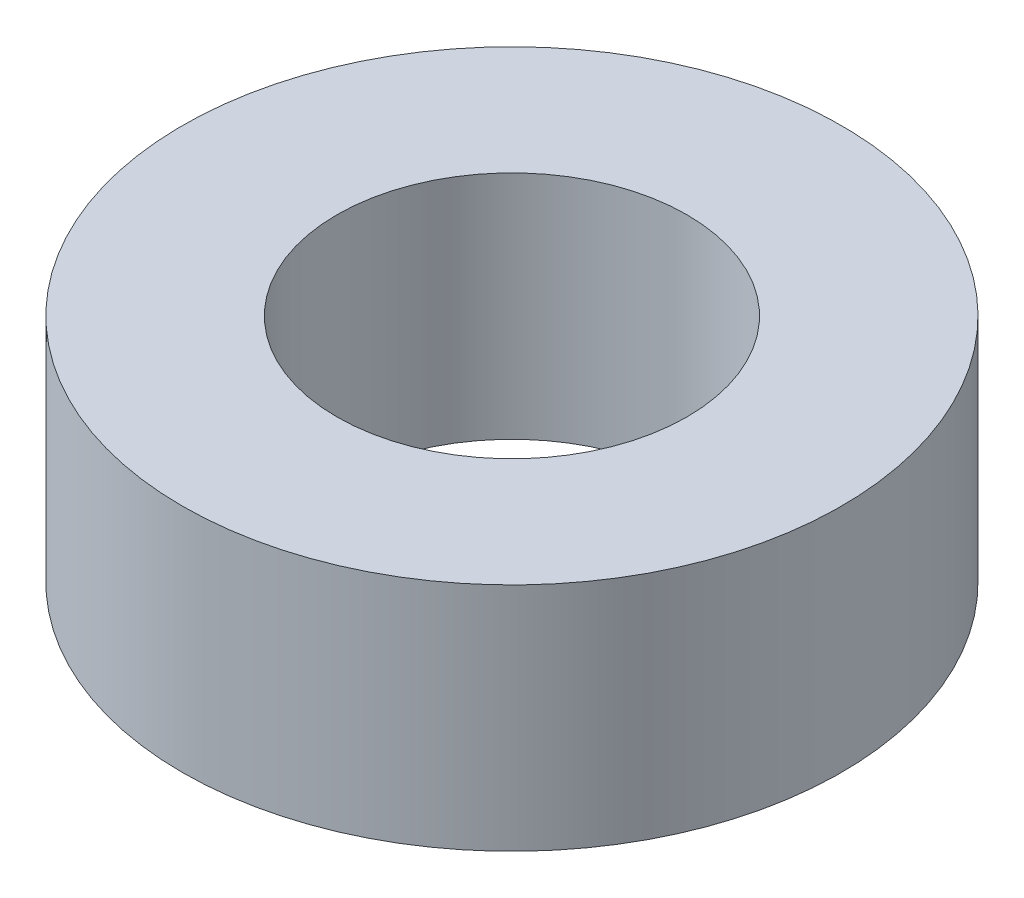
SolidWorks part; units mm, degrees
ref_plane "Alzado" through (0, 0, 0) normal (0, 0, 1) x (1, 0, 0)
ref_plane "Planta" through (0, 0, 0) normal (0, 1, 0) x (1, 0, 0)
ref_plane "Vista lateral" through (0, 0, 0) normal (1, 0, 0) x (0, 0, -1)
sketch "Croquis1" plane through (0, 0, 0) normal (0, 1, 0) x (1, 0, 0)
  circle A0 centre (0, 0) radius 4
  circle A1 centre (0, 0) radius 2.125
  dimension "D1" = 4.25
  dimension "D2" = 8
extrude "Saliente-Extruir1" add sketch "Croquis1" along normal blind 2.8
